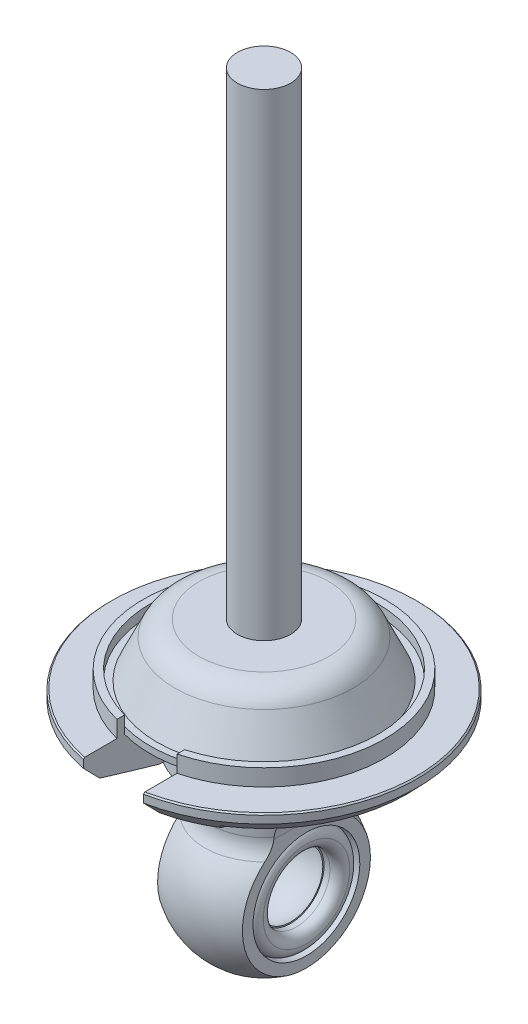
SolidWorks part; units mm, degrees
ref_plane "Front Plane" through (0, 0, 0) normal (0, 0, 1) x (1, 0, 0)
ref_plane "Top Plane" through (0, 0, 0) normal (0, 1, 0) x (1, 0, 0)
ref_plane "Right Plane" through (0, 0, 0) normal (1, 0, 0) x (0, 0, -1)
sketch "Sketch1" plane through (0, 0, 0) normal (1, 0, 0) x (0, 0, -1)
  line L0 (0, 0) -> (0, -276.2324) construction
  line L1 (0, -95.63) -> (3.99, -95.63)
  line L2 (3.99, -95.63) -> (3.99, -167.13)
  line L3 (3.99, -167.13) -> (9.7213, -167.13)
  line L4 (13.3465, -169.4395) -> (16, -175.13)
  line L5 (16, -175.13) -> (17, -175.13)
  line L6 (17, -175.13) -> (17, -173.63)
  line L7 (17, -173.63) -> (18.1, -173.63)
  line L8 (18.1, -173.63) -> (18.1, -176.13)
  line L9 (18.1, -176.13) -> (22.8, -176.13)
  line L10 (23, -176.33) -> (23, -177.48)
  line L11 (23, -177.48) -> (20.61, -179.97)
  line L12 (20.61, -179.97) -> (12, -182.63)
  line L13 (12, -182.63) -> (10.95, -182.63)
  line L14 (10.95, -182.63) -> (10.95, -184)
  line L15 (10.95, -184) -> (10.6946, -184.23)
  line L16 (10.6946, -184.23) -> (8, -184.23) construction
  line L17 (8, -187.2144) -> (8, -189.8193)
  line L18 (22.8, -176.13) -> (23, -176.33)
  line L19 (8, -184.23) -> (8, -187.2144) construction
  line L21 (0, -211.13) -> (0, -95.63)
  arc A0 (0, -211.13) -> (8.9032, -192.3511) centre (0, -199.63) ccw
  arc A1 (9.7213, -167.13) -> (13.3465, -169.4395) centre (9.7213, -171.13) cw
  arc A2 (0, -188.13) -> (0, -211.13) centre (0, -199.63) ccw construction
  arc A3 (8, -191.3686) -> (0, -188.13) centre (0, -199.63) ccw construction
  arc A4 (8, -189.8193) -> (8.9032, -192.3511) centre (12, -189.8193) ccw
  arc A6 (10.6946, -184.23) -> (8, -187.2144) centre (11, -187.2144) ccw
  point P16 (23, -176.13)
  point P34 (0, 0)
  point P35 (8, -187.0885)
  dimension "D2" = 23
  dimension "D23" = 4
  dimension "D24" = 4
  dimension "D25" = 3
  dimension "D1" = 199.63
  dimension "D3" = 16
  dimension "D4" = 15.4
  dimension "D5" = 0.23
  dimension "D6" = 21.9
  dimension "D7" = 42
  dimension "D8" = 17
  dimension "D9" = 12
  dimension "D10" = 20.61
  dimension "D11" = 19.66
  dimension "D12" = 22.15
  dimension "D13" = 23
  dimension "D14" = 23.5
  dimension "D15" = 18.1
  dimension "D16" = 26
  dimension "D17" = 1.1
  dimension "D18" = 24.5
  dimension "D19" = 16
  dimension "D20" = 32.5
  dimension "D21" = 65
  dimension "D22" = 3.99
  dimension "D26" = 104
revolve "Revolve1" add sketch "Sketch1" angle 360 about L0
sketch "Sketch2" plane through (0, 0, 0) normal (0, 0, 1) x (1, 0, 0)
  line L0 (0, 0) -> (0, -233.0262) construction
  line L1 (6.35, -209.2179) -> (6.35, -190.13)
  line L2 (22.5, -179.23) -> (22.5, -214.63)
  line L3 (9.35, -184.9338) -> (9.35, -182.63)
  line L4 (9.35, -182.63) -> (11, -182.63)
  line L5 (11, -182.63) -> (11, -180.03)
  line L6 (11.8, -179.23) -> (22.5, -179.23)
  line L7 (22.5, -214.63) -> (6.35, -214.63)
  line L8 (6.35, -214.63) -> (6.35, -209.2179)
  line L9 (-6.35, -214.63) -> (-6.35, -209.2179)
  line L10 (-22.5, -214.63) -> (-6.35, -214.63)
  line L11 (-11.8, -179.23) -> (-22.5, -179.23)
  line L12 (-11, -182.63) -> (-11, -180.03)
  line L13 (-9.35, -182.63) -> (-11, -182.63)
  line L14 (-9.35, -184.9338) -> (-9.35, -182.63)
  line L15 (-22.5, -179.23) -> (-22.5, -214.63)
  line L16 (-6.35, -209.2179) -> (-6.35, -190.13)
  arc A0 (-6.35, -209.2179) -> (6.35, -209.2179) centre (0, -199.63) ccw construction
  arc A1 (11, -180.03) -> (11.8, -179.23) centre (11.8, -180.03) cw
  arc A2 (6.35, -190.13) -> (9.35, -184.9338) centre (12.35, -190.13) cw
  arc A3 (-6.35, -190.13) -> (-9.35, -184.9338) centre (-12.35, -190.13) ccw
  arc A4 (-11, -180.03) -> (-11.8, -179.23) centre (-11.8, -180.03) ccw
  dimension "D2" = 23
  dimension "D4" = 6
  dimension "D12" = 0.8
  dimension "D1" = 199.63
  dimension "D3" = 12.7
  dimension "D5" = 9.5
  dimension "D6" = 18.7
  dimension "D7" = 17
  dimension "D8" = 11
  dimension "D9" = 20.4
  dimension "D10" = 45
  dimension "D11" = 15
extrude "Cut-Extrude6" cut sketch "Sketch2" against normal through all both and the other way through all
sketch "Sketch3" plane through (0, -182.63, 0) normal (0, -1, 0) x (1, 0, 0)
  line L0 (0, 0) -> (0, 28.2841) construction
  line L1 (4.5, 9.9826) -> (4.5, 28.2841)
  line L2 (4.5, 28.2841) -> (-4.5, 28.2841)
  line L3 (-4.5, 9.9826) -> (-4.5, 28.2841)
  arc A0 (9.35, 5.6991) -> (-9.35, 5.6991) centre (0, 0) ccw construction
  arc A1 (4.5, 9.9826) -> (-4.5, 9.9826) centre (0, 0) ccw
  dimension "D1" = 28.2841
  dimension "D2" = 9
extrude "Cut-Extrude7" cut sketch "Sketch3" against normal up to surface (6.5 mm away) up to face at (0, -176.13, 18.1)
sketch "Sketch4" plane through (0, -176.13, 0) normal (0, 1, 0) x (1, 0, 0)
  line L0 (0, 0) -> (0, -26.451) construction
  line L1 (-4.5, -16.3936) -> (-4.5, -17.5317)
  line L2 (4.5, -16.3936) -> (4.5, -17.5317)
  circle A0 centre (0, 0) radius 17 construction
  circle A1 centre (0, 0) radius 18.1 construction
  arc A2 (-4.5, -16.3936) -> (4.5, -16.3936) centre (0, 0) ccw
  arc A3 (-4.5, -17.5317) -> (4.5, -17.5317) centre (0, 0) ccw
  point P5 (0, 0)
  dimension "D1" = 9
extrude "Cut-Extrude8" cut sketch "Sketch4" along normal up to surface (2.5 mm away) up to face at (0, -173.63, 17)
sketch "Sketch5" plane through (6.35, 0, 0) normal (1, 0, 0) x (0, 0, -1)
  circle A0 centre (0, -199.63) radius 8
  arc A1 (-6.2406, -192.3511) -> (6.2406, -192.3511) centre (0, -199.63) ccw construction
  point P2 (0, -198.8225)
  dimension "D1" = 16
extrude "Cut-Extrude9" cut sketch "Sketch5" against normal through all
sketch "Sketch6" plane through (0, 0, 0) normal (1, 0, 0) x (0, 0, -1)
  circle A0 centre (0, -199.63) radius 8 construction
  circle A1 centre (0, -199.63) radius 8
extrude "Boss-Extrude1" add sketch "Sketch6" along normal mid plane 8
sketch "Sketch7" plane through (4, 0, 0) normal (1, 0, 0) x (0, 0, -1)
  circle A0 centre (0, -199.63) radius 7.95
  circle A1 centre (0, -199.63) radius 4.99
  dimension "D1" = 15.9
  dimension "D2" = 9.98
extrude "Boss-Extrude2" add sketch "Sketch7" along normal blind 2.35
fillet "Fillet1" radius 1.47 2 edges at (6.35, -199.63, -4.99) (6.35, -199.63, -7.95)
mirror "Mirror1" about plane through (0, 0, 0) normal (1, 0, 0) of "Fillet1", "Boss-Extrude2"
sketch "Sketch8" plane through (0, 0, 0) normal (1, 0, 0) x (0, 0, -1)
  line L0 (0, -211.13) -> (0, -182.63) construction
  line L1 (4.7958, -182.63) -> (-4.7958, -182.63) construction
  line L2 (0, -193.38) -> (0, -205.88)
  arc A0 (-8.9032, -192.3511) -> (8.9032, -192.3511) centre (0, -199.63) ccw construction
  arc A1 (0, -205.88) -> (0, -193.38) centre (0, -199.63) ccw
  dimension "D1" = 12.5
revolve "Cut-Revolve1" cut sketch "Sketch8" angle 360 about L0
